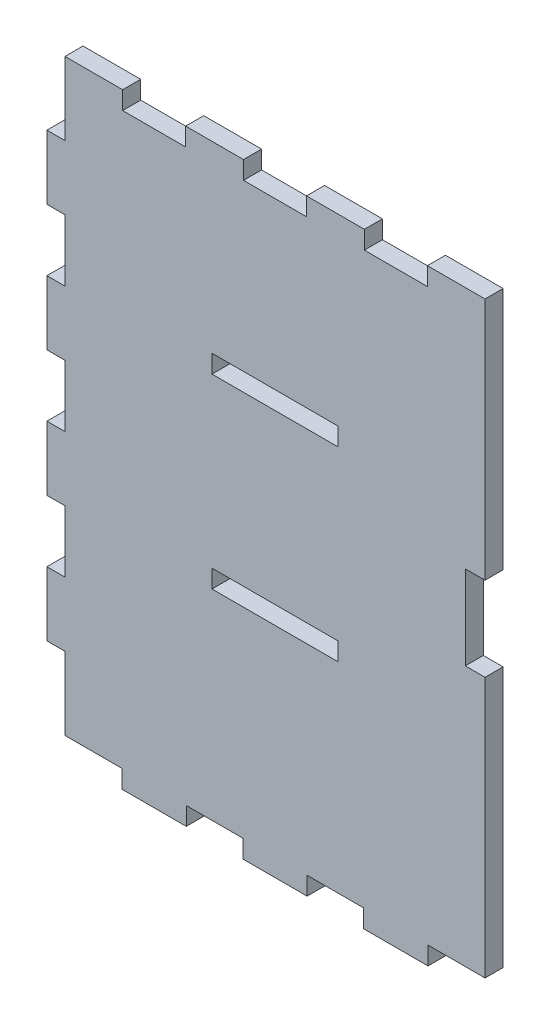
SolidWorks part; units mm, degrees
ref_plane "Front Plane" through (0, 0, 0) normal (0, 0, 1) x (1, 0, 0)
ref_plane "Top Plane" through (0, 0, 0) normal (0, 1, 0) x (1, 0, 0)
ref_plane "Right Plane" through (0, 0, 0) normal (1, 0, 0) x (0, 0, -1)
sketch "Sketch2" plane through (0, 0, 0) normal (0, 0, 1) x (1, 0, 0)
  line L0 (100, 140) -> (100, 82)
  line L1 (0, 0) -> (13.575, 0)
  line L3 (0, 140) -> (13.725, 140)
  line L34 (28.725, 140) -> (42.5, 140)
  line L35 (13.725, 135.7) -> (28.725, 135.7)
  line L36 (13.725, 135.7) -> (13.725, 140)
  line L38 (28.725, 135.7) -> (28.725, 140)
  line L39 (57.5, 135.7) -> (57.5, 140)
  line L40 (42.5, 135.7) -> (57.5, 135.7)
  line L41 (42.5, 135.7) -> (42.5, 140)
  line L42 (86.275, 135.7) -> (86.275, 140)
  line L43 (71.275, 135.7) -> (86.275, 135.7)
  line L44 (71.275, 135.7) -> (71.275, 140)
  line L45 (57.5, 140) -> (71.275, 140)
  line L46 (86.275, 140) -> (100, 140)
  line L47 (28.875, 0) -> (42.35, 0)
  line L48 (13.575, -4.3) -> (28.875, -4.3)
  line L49 (13.575, -4.3) -> (13.575, 0)
  line L51 (28.875, -4.3) -> (28.875, 0)
  line L52 (57.65, -4.3) -> (57.65, 0)
  line L53 (42.35, -4.3) -> (57.65, -4.3)
  line L54 (42.35, -4.3) -> (42.35, 0)
  line L55 (86.425, -4.3) -> (86.425, 0)
  line L56 (71.125, -4.3) -> (86.425, -4.3)
  line L57 (71.125, -4.3) -> (71.125, 0)
  line L58 (57.65, 0) -> (71.125, 0)
  line L59 (86.425, 0) -> (100, 0)
  line L60 (0, 122.65) -> (0, 140)
  line L61 (-4.3, 107.35) -> (0, 107.35)
  line L62 (-4.3, 107.35) -> (-4.3, 122.65)
  line L63 (-4.3, 122.65) -> (0, 122.65)
  line L65 (-4.3, 77.35) -> (0, 77.35)
  line L66 (-4.3, 77.35) -> (-4.3, 92.65)
  line L67 (-4.3, 92.65) -> (0, 92.65)
  line L68 (-4.3, 47.35) -> (0, 47.35)
  line L69 (-4.3, 47.35) -> (-4.3, 62.65)
  line L70 (-4.3, 62.65) -> (0, 62.65)
  line L71 (-4.3, 17.35) -> (0, 17.35)
  line L72 (-4.3, 17.35) -> (-4.3, 32.65)
  line L73 (-4.3, 32.65) -> (0, 32.65)
  line L77 (0, 92.65) -> (0, 107.35)
  line L78 (0, 62.65) -> (0, 77.35)
  line L79 (0, 32.65) -> (0, 47.35)
  line L80 (0, 0) -> (0, 17.35)
  line L81 (35, 52) -> (65, 52)
  line L82 (35, 47.7) -> (65, 47.7)
  line L83 (35, 96.3) -> (65, 96.3)
  line L84 (35, 92) -> (65, 92)
  line L85 (35, 47.7) -> (35, 52)
  line L86 (65, 47.7) -> (65, 52)
  line L87 (35, 92) -> (35, 96.3)
  line L88 (65, 92) -> (65, 96.3)
  line L89 (50, 92) -> (50, 52) construction
  line L90 (95.3, 62) -> (100, 62)
  line L91 (95.3, 62) -> (95.3, 82)
  line L92 (95.3, 82) -> (100, 82)
  line L96 (100, 62) -> (100, 0)
  point P5 (-4.3, 115)
  point P34 (50, 52)
  point P49 (95.3, 72)
  point P63 (-4.3, 85)
  point P67 (50, 72)
  point P68 (21.225, -4.3)
  point P69 (50, -4.3)
  point P70 (21.225, 135.7)
  point P71 (50, 135.7)
  dimension "D2" = 100
  dimension "D3" = 140
  dimension "D4" = 4.3
  dimension "D5" = 15.3
  dimension "D6" = 25
  dimension "D7" = 4
  dimension "D8" = 15
  dimension "D9" = 4.3
  dimension "D10" = 21.225
  dimension "D11" = 3
  dimension "D12" = 28.775
  dimension "D13" = 15.3
  dimension "D14" = 4.3
  dimension "D15" = 3
  dimension "D16" = 21.225
  dimension "D17" = 30
  dimension "D18" = 4.3
  dimension "D19" = 4.3
  dimension "D20" = 47.7
  dimension "D21" = 40
  dimension "D22" = 30
  dimension "D23" = 50
  dimension "D24" = 20
  dimension "D25" = 4.7
  dimension "D26" = 28.775
extrude "Boss-Extrude1" add sketch "Sketch2" along normal blind 4.3
